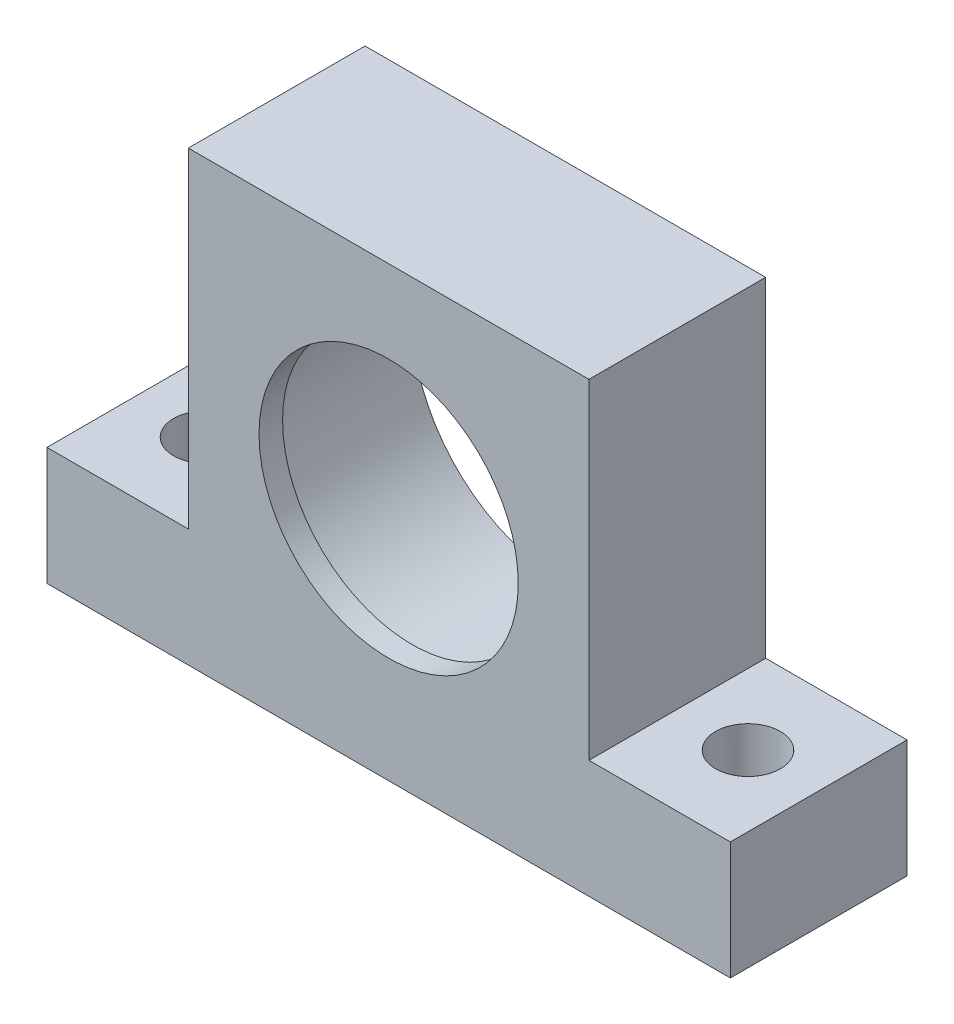
SolidWorks part; units mm, degrees
ref_plane "前视基准面" through (0, 0, 0) normal (0, 0, 1) x (1, 0, 0)
ref_plane "上视基准面" through (0, 0, 0) normal (0, 1, 0) x (1, 0, 0)
ref_plane "右视基准面" through (0, 0, 0) normal (1, 0, 0) x (0, 0, -1)
sketch "草图1" plane through (0, 0, 0) normal (0, 0, 1) x (1, 0, 0)
  line L0 (29, 0) -> (-29, 0)
  line L1 (-29, 0) -> (-29, 10)
  line L2 (-29, 10) -> (-17, 10)
  line L3 (-17, 10) -> (-17, 38)
  line L4 (-17, 38) -> (17, 38)
  line L5 (0, 38) -> (0, 0) construction
  line L6 (17, 10) -> (17, 38)
  line L7 (29, 10) -> (17, 10)
  line L8 (29, 0) -> (29, 10)
  dimension "D1" = 58
  dimension "D2" = 10
  dimension "D3" = 34
  dimension "D4" = 38
extrude "凸台-拉伸1" add sketch "草图1" along normal blind 15
sketch "草图2" plane through (0, 0, 0) normal (0, 0, -1) x (-1, 0, 0)
  line L0 (0, 0) -> (0, 38) construction
  line L1 (-17, 38) -> (17, 38) construction
  line L2 (29, 0) -> (-29, 0) construction
  circle A0 centre (0, 20) radius 11
  dimension "D1" = 22
  dimension "D2" = 20
extrude "切除-拉伸1" cut sketch "草图2" against normal through all
sketch "草图3" plane through (0, 0, 0) normal (0, 0, -1) x (-1, 0, 0)
  circle A0 centre (0, 20) radius 13
  dimension "D1" = 26
extrude "切除-拉伸2" cut sketch "草图3" against normal offset from surface (13 mm away) 2 up to face at (-11, 20, 15)
sketch "草图4" plane through (0, 0, 0) normal (0, -1, 0) x (1, 0, 0)
  line L0 (-29, 7.5) -> (29, 7.5) construction
  line L1 (-29, 15) -> (-29, 0) construction
  line L2 (29, 15) -> (29, 0) construction
  line L3 (0, 7.5) -> (0, 15) construction
  line L4 (-29, 15) -> (29, 15) construction
  circle A0 centre (-23, 7.5) radius 2.75
  circle A1 centre (23, 7.5) radius 2.75
  dimension "D1" = 5.5
  dimension "D2" = 46
extrude "切除-拉伸3" cut sketch "草图4" against normal through all
